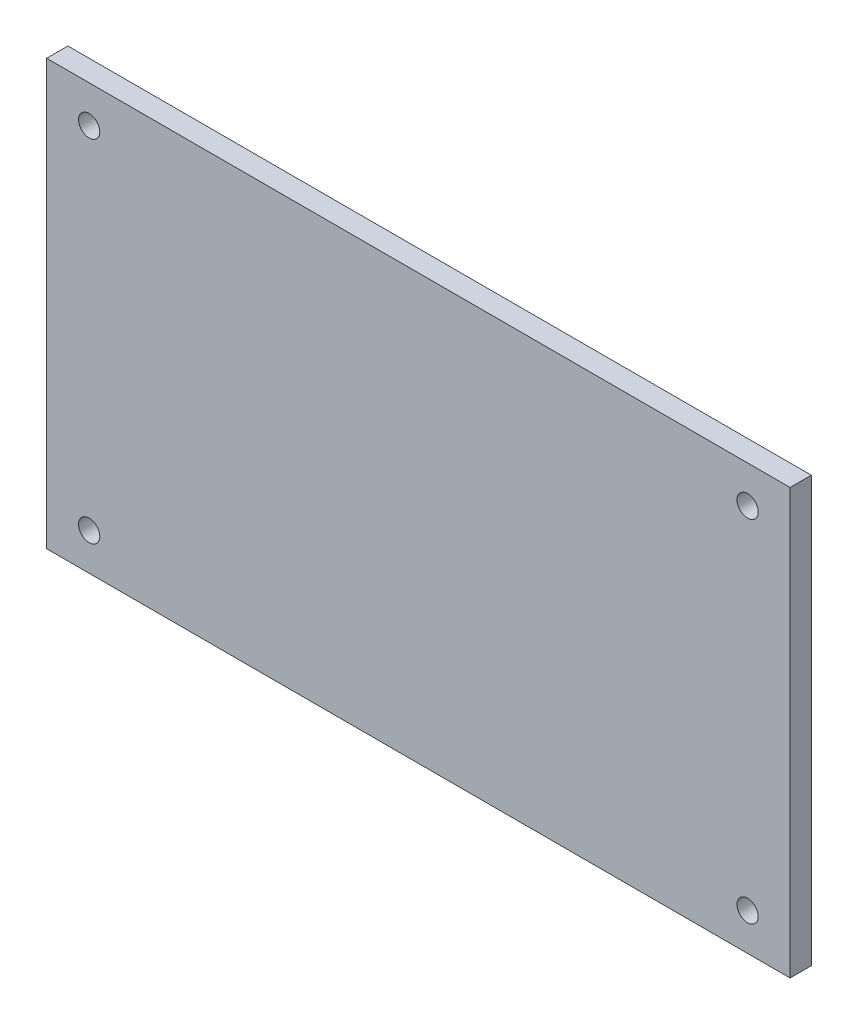
SolidWorks part; units mm, degrees
ref_plane "Front Plane" through (0, 0, 0) normal (0, 0, 1) x (1, 0, 0)
ref_plane "Top Plane" through (0, 0, 0) normal (0, 1, 0) x (1, 0, 0)
ref_plane "Right Plane" through (0, 0, 0) normal (1, 0, 0) x (0, 0, -1)
sketch "Sketch1" plane through (0, 0, 0) normal (0, 0, 1) x (1, 0, 0)
  line L1 (-52.5, 30) -> (52.5, 30)
  line L2 (-52.5, 30) -> (-52.5, -30)
  line L3 (-52.5, -30) -> (52.5, -30)
  line L4 (52.5, 30) -> (52.5, -30)
  line L5 (-52.5, 30) -> (52.5, -30) construction
  line L6 (-52.5, -30) -> (52.5, 30) construction
  point P0 (0, 0)
  dimension "D1" = 105
  dimension "D2" = 60
extrude "Boss-Extrude1" add sketch "Sketch1" along normal blind 3
sketch "Sketch2" plane through (0, 0, 0) normal (0, 0, -1) x (-1, 0, 0)
  circle A0 centre (-46.5, 24.75) radius 1.5 construction
  circle A1 centre (-46.5, -24.75) radius 1.5 construction
  circle A2 centre (46.5, -24.75) radius 1.5 construction
  circle A3 centre (46.5, 24.75) radius 1.5 construction
  circle A4 centre (-46.5, 24.75) radius 1.5
  circle A5 centre (-46.5, -24.75) radius 1.5
  circle A6 centre (46.5, -24.75) radius 1.5
  circle A7 centre (46.5, 24.75) radius 1.5
extrude "Cut-Extrude1" cut sketch "Sketch2" against normal through all
